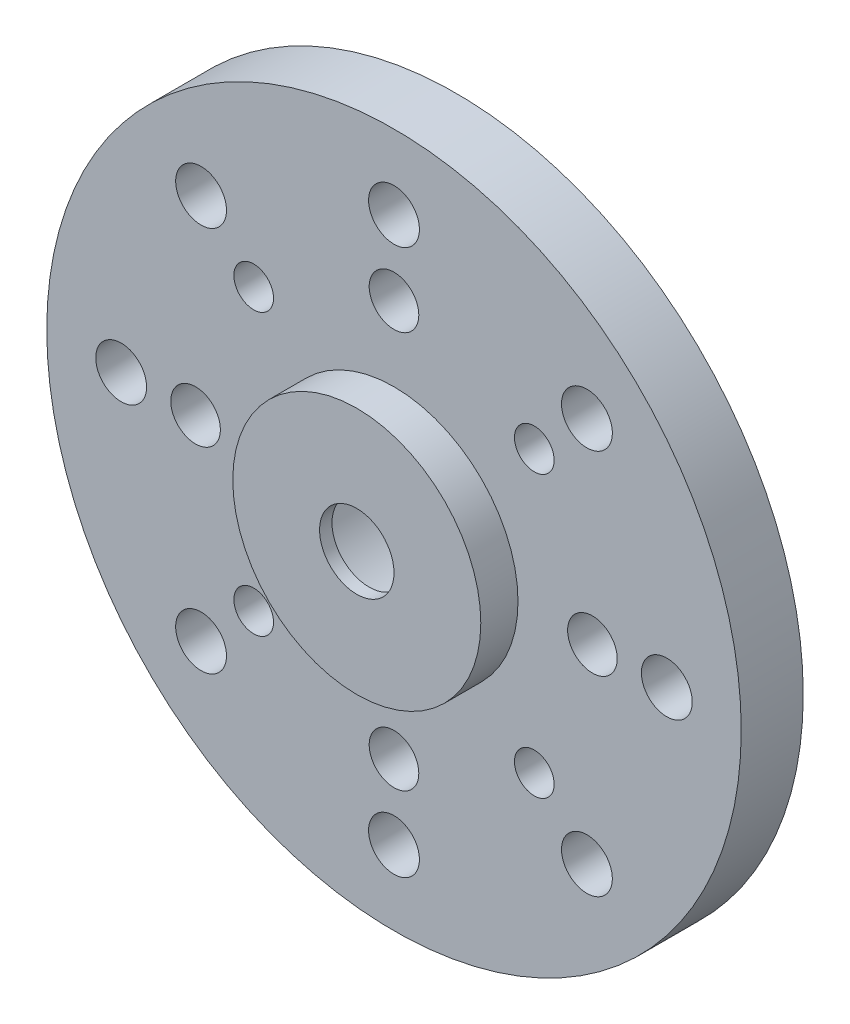
SolidWorks part; units mm, degrees
material "1060 Alloy"
ref_plane "Front Plane" through (0, 0, 0) normal (0, 0, 1) x (1, 0, 0)
ref_plane "Top Plane" through (0, 0, 0) normal (0, 1, 0) x (1, 0, 0)
ref_plane "Right Plane" through (0, 0, 0) normal (1, 0, 0) x (0, 0, -1)
ref_plane "Plane1" through (0, 0, 0) normal (0, -1, 0) x (1, 0, 0)
sketch "Sketch1" plane through (0, 0, 0) normal (0, -1, 0) x (1, 0, 0)
  line L0 (2.75, 25) -> (0, 25)
  line L1 (0, 24.5164) -> (0, 20.5)
  line L2 (0, 20.5) -> (5.5, 20.5)
  line L3 (5.5, 20.5) -> (5.5, 21)
  line L4 (5.5, 21) -> (14, 21)
  line L5 (14, 21) -> (14, 23.5)
  line L6 (14, 23.5) -> (5, 23.5)
  line L7 (5, 23.5) -> (5, 25)
  line L8 (5, 25) -> (2.75, 25)
  line L9 (0, 25) -> (0, 24.5164)
  line L10 (0, 24.5164) -> (0, 20.5) construction
  dimension "D1" = 2.5
  dimension "D2" = 9
  dimension "D3" = 8.5
  dimension "D4" = 5
  dimension "D5" = 1.5
  dimension "D6" = 0.5
  dimension "D8" = 4.0164
revolve "Revolve1" add sketch "Sketch1" angle 360 about L10
hole_wizard "Ø3.0 (3) Diameter Hole1" positions "Sketch2" profile "Sketch4" hole size "Ø3.0" standard "ISO" end condition up to next
sketch "Sketch2" plane through (0, 0, 25) normal (0, 0, 1) x (1, 0, 0)
  point P0 (0, 0)
sketch "Sketch4" plane through (0, 0, 25) normal (1, 0, 0) x (0, -1, 0)
  line L0 (0, 0) -> (0, 4.5)
  line L1 (0, 4.5) -> (1.5, 4.5)
  line L2 (1.5, 4.5) -> (1.5, 0)
  line L5 (1.5, 0) -> (0, 0)
  line L11 (0, -6.35) -> (0, 107.95) construction
  dimension "Thru Hole Dia." = 3
  dimension "Thru Hole Depth" = 4.5
sketch "Sketch5" plane through (0, 0, 23.5) normal (0, 0, 1) x (1, 0, 0)
  line L0 (0, 0) -> (0, 8) construction
  line L1 (0, 0) -> (5.6569, 5.6569) construction
  circle A0 centre (0, 0) radius 8 construction
  circle A1 centre (0, 0) radius 11 construction
  dimension "D1" = 45
hole_wizard "M2.5 Tapped Hole1" positions "Sketch6" profile "Sketch7" tap size "M2.5" standard "ISO" end condition through all
sketch "Sketch6" plane through (0, 0, 23.5) normal (0, 0, 1) x (1, 0, 0)
  circle A0 centre (0, 0) radius 11 construction
  point P0 (0, 11)
sketch "Sketch7" plane through (0, 11, 23.5) normal (1, 0, 0) x (0, -1, 0)
  line L0 (0, 0) -> (0, 3)
  line L1 (0, 3) -> (1.025, 3)
  line L2 (1.025, 3) -> (1.025, 0)
  line L5 (1.025, 0) -> (0, 0)
  line L11 (0, -6.35) -> (0, 107.95) construction
  dimension "Thru Tap Drill Dia." = 2.05
  dimension "Thru Tap Drill Depth" = 3
cosmetic thread "Hole Thread1" parameters "D2"=2.5
pattern_circular "CirPattern1" count 8 over 360 about axis through (0, 0, 0) along (0, 0, 1) of "M2.5 Tapped Hole1"
hole_wizard "Ø2.0 (2) Diameter Hole1" positions "Sketch8" profile "Sketch9" hole size "Ø2.0" standard "ISO" end condition through all
sketch "Sketch8" plane through (0, 0, 25) normal (0, 0, 1) x (1, 0, 0)
  circle A0 centre (0, 0) radius 8 construction
  point P0 (0, 8)
  point P4 (8, 0)
  point P6 (0, -8)
  point P8 (-8, 0)
sketch "Sketch9" plane through (0, 8, 25) normal (1, 0, 0) x (0, -1, 0)
  line L0 (0, 0) -> (0, 4.5)
  line L1 (0, 4.5) -> (1, 4.5)
  line L2 (1, 4.5) -> (1, 0)
  line L5 (1, 0) -> (0, 0)
  line L11 (0, -6.35) -> (0, 107.95) construction
  dimension "Thru Hole Dia." = 2
  dimension "Thru Hole Depth" = 4.5
hole_wizard "M2 Tapped Hole1" positions "Sketch10" profile "Sketch11" tap size "M2" standard "ISO" end condition through all
sketch "Sketch10" plane through (0, 0, 23.5) normal (0, 0, 1) x (1, 0, 0)
  point P9 (5.6569, 5.6569)
sketch "Sketch11" plane through (5.6569, 5.6569, 23.5) normal (1, 0, 0) x (0, -1, 0)
  line L0 (0, 0) -> (0, 3)
  line L1 (0, 3) -> (0.8, 3)
  line L2 (0.8, 3) -> (0.8, 0)
  line L5 (0.8, 0) -> (0, 0)
  line L11 (0, -6.35) -> (0, 107.95) construction
  dimension "Thru Tap Drill Dia." = 1.6
  dimension "Thru Tap Drill Depth" = 3
cosmetic thread "Hole Thread2" parameters "D2"=2
pattern_circular "CirPattern2" count 4 over 360 about axis through (0, 0, 0) along (0, 0, 1) of "M2 Tapped Hole1"
sketch "Sketch14" plane through (0, 0, 20.5) normal (0, 0, -1) x (-1, 0, 0)
  circle A0 centre (0, 0) radius 3.5
extrude "Cut-Extrude1" cut sketch "Sketch14" against normal blind 4
